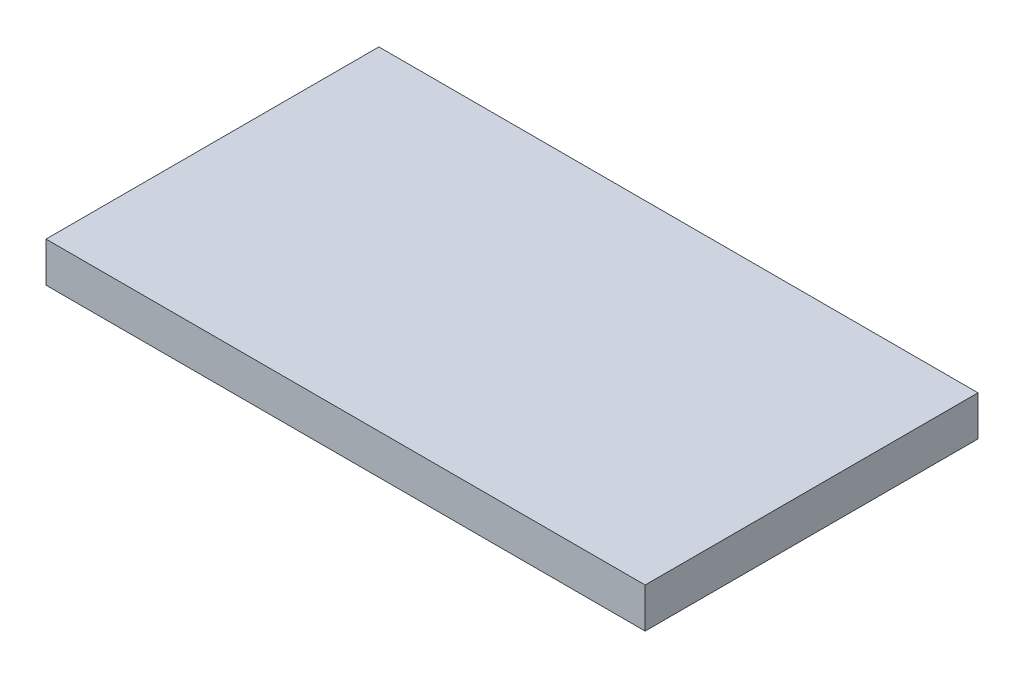
SolidWorks part; units mm, degrees
material "MDF"
ref_plane "Alzado" through (0, 0, 0) normal (0, 0, 1) x (1, 0, 0)
ref_plane "Planta" through (0, 0, 0) normal (0, 1, 0) x (1, 0, 0)
ref_plane "Vista lateral" through (0, 0, 0) normal (1, 0, 0) x (0, 0, -1)
sketch "Croquis1" plane through (0, 0, 0) normal (0, 1, 0) x (1, 0, 0)
  line L1 (-22.5, 12.5) -> (22.5, 12.5)
  line L2 (-22.5, 12.5) -> (-22.5, -12.5)
  line L3 (-22.5, -12.5) -> (22.5, -12.5)
  line L4 (22.5, 12.5) -> (22.5, -12.5)
  line L5 (-22.5, 12.5) -> (22.5, -12.5) construction
  line L6 (-22.5, -12.5) -> (22.5, 12.5) construction
  point P0 (0, 0)
  dimension "D1" = 45
  dimension "D2" = 25
extrude "Saliente-Extruir1" add sketch "Croquis1" along normal mid plane 3
